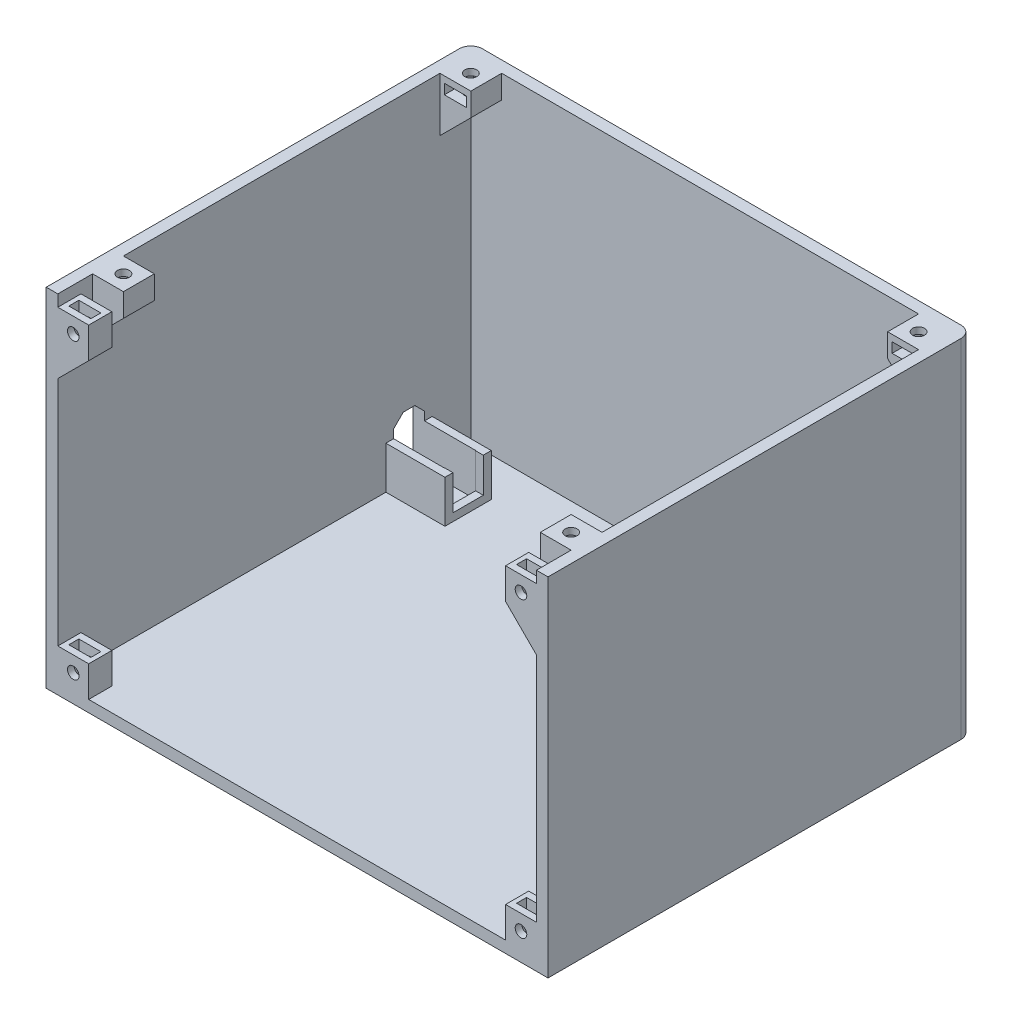
SolidWorks part; units mm, degrees
ref_plane "Спереди" through (0, 0, 0) normal (0, 0, 1) x (1, 0, 0)
ref_plane "Сверху" through (0, 0, 0) normal (0, 1, 0) x (1, 0, 0)
ref_plane "Справа" through (0, 0, 0) normal (1, 0, 0) x (0, 0, -1)
sketch "Эскиз2" plane through (0, 0, 0) normal (0, 0, 1) x (1, 0, 0)
  line L1 (-65, 45) -> (65, 45)
  line L2 (-65, 45) -> (-65, -45)
  line L3 (-65, -45) -> (65, -45)
  line L4 (65, 45) -> (65, -45)
  line L5 (-65, 45) -> (65, -45) construction
  line L6 (-65, -45) -> (65, 45) construction
  point P0 (0, 0)
  dimension "D1" = 90
  dimension "D2" = 130
extrude "Бобышка-Вытянуть1" add sketch "Эскиз2" along normal blind 110
sketch "Эскиз3" plane through (0, 45, 0) normal (0, 1, 0) x (1, 0, 0)
  line L0 (-65, -110) -> (-65, 0) construction
  line L1 (-62, -3) -> (62, -3)
  line L2 (-62, -3) -> (-62, -110)
  line L3 (-62, -110) -> (62, -110)
  line L4 (62, -3) -> (62, -110)
  line L5 (-62, -3) -> (62, -110) construction
  line L6 (-62, -110) -> (62, -3) construction
  line L8 (65, 0) -> (-65, 0) construction
  point P0 (0, -56.5)
  dimension "D1" = 107
  dimension "D2" = 124
  dimension "D3" = 3
  dimension "D4" = 3
extrude "Вырез-Вытянуть1" cut sketch "Эскиз3" against normal blind 87
sketch "Эскиз13" plane through (-65, 0, 0) normal (-1, 0, 0) x (0, 0, 1)
  line L0 (15, -42) -> (23, -42)
  line L1 (23, -42) -> (23, -28.8)
  line L2 (23, -28.8) -> (20.5058, -26.3)
  line L3 (20.5058, -26.3) -> (17.4942, -26.3)
  line L4 (17.4942, -26.3) -> (15, -28.8)
  line L5 (15, -28.8) -> (15, -42)
  line L6 (0, 45) -> (0, -45) construction
  line L7 (110, -45) -> (0, -45) construction
  point P6 (19, -26.3)
  point P7 (19, -42)
  dimension "D1" = 8
  dimension "D2" = 15.7
  dimension "D3" = 2.5
  dimension "D4" = 15
  dimension "D5" = 3
extrude "Вырез-Вытянуть5" cut sketch "Эскиз13" against normal up to next
sketch "Эскиз15" plane through (0, -42, 0) normal (0, 1, 0) x (1, 0, 0)
  line L0 (-62, -25) -> (-46.7, -25)
  line L1 (-46.7, -25) -> (-46.7, -13)
  line L2 (-46.7, -13) -> (-62, -13)
  line L3 (-62, -13) -> (-62, -15)
  line L4 (-62, -15) -> (-48.7, -15)
  line L5 (-48.7, -15) -> (-48.7, -23)
  line L6 (-48.7, -23) -> (-62, -23)
  line L7 (-62, -25) -> (-62, -23)
  line L9 (-62, -3) -> (-62, -15) construction
  line L11 (62, -3) -> (-62, -3) construction
  dimension "D1" = 8
  dimension "D2" = 2
  dimension "D3" = 2
  dimension "D4" = 2
  dimension "D5" = 15.3
  dimension "D6" = 10
extrude "Бобышка-Вытянуть5" add sketch "Эскиз15" along normal blind 11
sketch "Эскиз16" plane through (0, -31, 0) normal (0, 1, 0) x (1, 0, 0)
  line L0 (-46.7, -25) -> (-46.7, -13) construction
  line L2 (-49.6087, -15.0713) -> (-43.7913, -15.0713)
  line L3 (-49.6087, -15.0713) -> (-49.6087, -22.9287)
  line L4 (-49.6087, -22.9287) -> (-43.7913, -22.9287)
  line L5 (-43.7913, -15.0713) -> (-43.7913, -22.9287)
  line L6 (-49.6087, -15.0713) -> (-43.7913, -22.9287) construction
  line L7 (-49.6087, -22.9287) -> (-43.7913, -15.0713) construction
  point P3 (-46.7, -19)
  dimension "D1" = 7.8574
  dimension "D2" = 5.8174
extrude "Вырез-Вытянуть6" cut sketch "Эскиз16" against normal blind 9
fillet "Скругление8" radius 3 1 edges at (-65, 0, 0)
fillet "Скругление9" radius 3 1 edges at (65, 0, 0)
sketch "Эскиз17" plane through (0, 0, 110) normal (0, 0, 1) x (1, 0, 0)
  line L1 (-62, -42) -> (-54, -42)
  line L2 (-62, -42) -> (-62, -34)
  line L3 (-62, -34) -> (-54, -34)
  line L4 (-54, -42) -> (-54, -34)
  circle A0 centre (-58, -38) radius 1.5
  dimension "D3" = 3
  dimension "D1" = 8
  dimension "D2" = 8
extrude "Бобышка-Вытянуть6" add sketch "Эскиз17" against normal blind 6
pattern_linear "Линейный массив1" count 2 spacing 116 along (1, 0, 0) count 2 spacing 76 along (0, 1, 0) of "Бобышка-Вытянуть6"
sketch "Эскиз18" plane through (0, 0, 110) normal (0, 0, 1) x (1, 0, 0)
  line L0 (-54, 34) -> (-62, 34)
  line L1 (-62, 34) -> (-54, 34) construction
  line L2 (-62, 34) -> (-62, 26)
  line L3 (-62, -42) -> (-62, 45) construction
  line L4 (-62, 26) -> (-54, 34)
  dimension "D1" = 8
  dimension "D2" = 8
extrude "Бобышка-Вытянуть7" add sketch "Эскиз18" against normal blind 6
sketch "Эскиз19" plane through (0, 0, 110) normal (0, 0, 1) x (1, 0, 0)
  line L0 (62, 34) -> (54, 34)
  line L1 (54, 34) -> (62, 26)
  line L2 (62, -42) -> (62, 45) construction
  line L3 (62, 26) -> (62, 34)
  dimension "D1" = 8
  dimension "D2" = 8
extrude "Бобышка-Вытянуть8" add sketch "Эскиз19" against normal blind 6
sketch "Эскиз20" plane through (0, -34, 0) normal (0, 1, 0) x (1, 0, 0)
  line L0 (-54, -104) -> (-62, -104) construction
  line L1 (-60.85, -105.7) -> (-55.15, -105.7)
  line L2 (-60.85, -105.7) -> (-60.85, -108.3)
  line L3 (-60.85, -108.3) -> (-55.15, -108.3)
  line L4 (-55.15, -105.7) -> (-55.15, -108.3)
  line L5 (-60.85, -105.7) -> (-55.15, -108.3) construction
  line L6 (-60.85, -108.3) -> (-55.15, -105.7) construction
  line L8 (-54, -104) -> (-54, -110) construction
  point P0 (-58, -107)
  point P5 (0, 0)
  point P8 (0, 0)
  point P11 (-58, -104)
  point P12 (-54, -107)
  point P13 (-74.9882, -107.6912)
  dimension "D1" = 5.7
  dimension "D2" = 2.6
extrude "Вырез-Вытянуть7" cut sketch "Эскиз20" against normal blind 7.5
pattern_linear "Линейный массив2" count 2 spacing 116 along (1, 0, 0) count 2 spacing 76 along (0, 1, 0) of "Вырез-Вытянуть7"
sketch "Эскиз23" plane through (0, 45, 0) normal (0, 1, 0) x (1, 0, 0)
  line L0 (-65, -110) -> (-65, -3) construction
  line L1 (-62, -3) -> (-54, -3)
  line L2 (-62, -3) -> (-62, -11)
  line L3 (-62, -11) -> (-54, -11)
  line L4 (-54, -3) -> (-54, -11)
  line L5 (62, 0) -> (-62, 0) construction
  circle A0 centre (-58, -7) radius 1.55
  dimension "D3" = 3.1
  dimension "D1" = 8
  dimension "D2" = 8
  dimension "D4" = 7
  dimension "D5" = 7
extrude "Бобышка-Вытянуть9" add sketch "Эскиз23" against normal blind 6 separate body
pattern_linear "Линейный массив3" count 2 spacing 116 along (1, 0, 0) count 2 spacing 90 along (0, 0, 1) of "Бобышка-Вытянуть9"
sketch "Эскиз24" plane through (0, 0, 3) normal (0, 0, 1) x (1, 0, 0)
  line L0 (-54, 39) -> (-62, 39)
  line L1 (-62, 39) -> (-62, 31)
  line L2 (-62, -42) -> (-62, 45) construction
  line L3 (-62, 31) -> (-54, 39)
  dimension "D1" = 8
  dimension "D2" = 8
extrude "Бобышка-Вытянуть10" add sketch "Эскиз24" along normal blind 8
sketch "Эскиз25" plane through (0, 0, 3) normal (0, 0, 1) x (1, 0, 0)
  line L0 (54, 39) -> (62, 39)
  line L1 (62, 39) -> (62, 31)
  line L2 (62, -42) -> (62, 45) construction
  line L3 (62, 31) -> (54, 39)
  dimension "D1" = 8
  dimension "D2" = 8
extrude "Бобышка-Вытянуть11" add sketch "Эскиз25" along normal blind 8
pattern_linear "Линейный массив4" count 2 spacing 90 along (0, 0, 1) of "Бобышка-Вытянуть10"
pattern_linear "Линейный массив5" count 2 spacing 90 along (0, 0, 1) of "Бобышка-Вытянуть11"
sketch "Эскиз27" plane through (0, 0, 11) normal (0, 0, 1) x (1, 0, 0)
  line L0 (-65, 45) -> (-65, -45) construction
  line L1 (-60.85, 43.3364) -> (-55.15, 43.3364)
  line L2 (-60.85, 43.3364) -> (-60.85, 40.7364)
  line L3 (-60.85, 40.7364) -> (-55.15, 40.7364)
  line L4 (-55.15, 43.3364) -> (-55.15, 40.7364)
  line L5 (-60.85, 43.3364) -> (-55.15, 40.7364) construction
  line L6 (-60.85, 40.7364) -> (-55.15, 43.3364) construction
  line L7 (-62, 45) -> (-54, 45) construction
  point P0 (-58, 42)
  point P5 (0, 0)
  point P6 (0, 0)
  point P7 (0, 0)
  point P10 (-58, 43.3364)
  dimension "D1" = 5.7
  dimension "D2" = 2.6
  dimension "D3" = 7
  dimension "D4" = 3
extrude "Вырез-Вытянуть8" cut sketch "Эскиз27" against normal blind 7.5
pattern_linear "Линейный массив6" count 2 spacing 116 along (1, 0, 0) of "Вырез-Вытянуть8"
sketch "Эскиз28" plane through (0, 0, 93) normal (0, 0, -1) x (-1, 0, 0)
  line L0 (-65, -45) -> (-65, 45) construction
  line L1 (-60.85, 43.3) -> (-55.15, 43.3)
  line L2 (-60.85, 43.3) -> (-60.85, 40.7)
  line L3 (-60.85, 40.7) -> (-55.15, 40.7)
  line L4 (-55.15, 43.3) -> (-55.15, 40.7)
  line L5 (-60.85, 43.3) -> (-55.15, 40.7) construction
  line L6 (-60.85, 40.7) -> (-55.15, 43.3) construction
  line L7 (-62, 45) -> (-54, 45) construction
  point P0 (-58, 42)
  point P5 (0, 0)
  dimension "D1" = 5.7
  dimension "D2" = 2.6
  dimension "D3" = 7
  dimension "D4" = 3
extrude "Вырез-Вытянуть9" cut sketch "Эскиз28" against normal blind 7.5
pattern_linear "Линейный массив7" count 2 spacing 116 along (-1, 0, 0) of "Вырез-Вытянуть9"
sketch "Эскиз29" plane through (0, 45, 0) normal (0, 1, 0) x (1, 0, 0)
  line L0 (-58, -97) -> (-58, -90.1429) construction
  line L1 (-58, -90.1429) -> (-58, -97) construction
  line L2 (-58, -97) -> (-68.357, -97) construction
  line L3 (-65, -110) -> (-65, -3) construction
  line L4 (-62, -110) -> (-65, -110) construction
  dimension "D1" = 7
  dimension "D2" = 13
